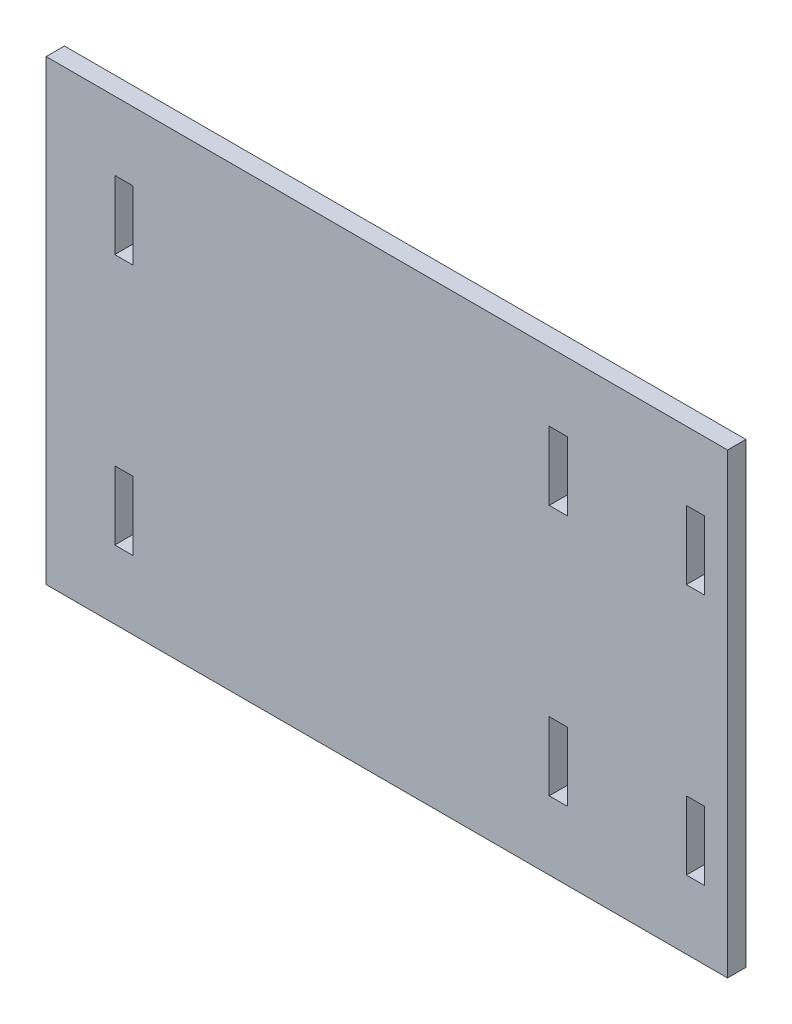
SolidWorks part; units mm, degrees
ref_plane "Front Plane" through (0, 0, 0) normal (0, 0, 1) x (1, 0, 0)
ref_plane "Top Plane" through (0, 0, 0) normal (0, 1, 0) x (1, 0, 0)
ref_plane "Right Plane" through (0, 0, 0) normal (1, 0, 0) x (0, 0, -1)
sketch "Sketch1" plane through (0, 0, 0) normal (0, 0, 1) x (1, 0, 0)
  line L0 (0, 66.0849) -> (0, -70.4198) construction
  line L1 (-64.5, -50) -> (64.5, -50)
  line L3 (-64.5, 50) -> (64.5, 50)
  line L7 (45.5, 35) -> (49.5, 35)
  line L8 (45.5, 35) -> (45.5, 20)
  line L9 (45.5, 20) -> (49.5, 20)
  line L10 (49.5, 35) -> (49.5, 20)
  line L11 (-103.5149, 0) -> (102.2922, 0) construction
  line L12 (45.5, -20) -> (49.5, -20)
  line L13 (45.5, -35) -> (45.5, -20)
  line L14 (49.5, -35) -> (49.5, -20)
  line L15 (45.5, -35) -> (49.5, -35)
  line L16 (-45.5, 35) -> (-49.5, 35)
  line L17 (-45.5, 35) -> (-45.5, 20)
  line L18 (-49.5, 35) -> (-49.5, 20)
  line L19 (-45.5, 20) -> (-49.5, 20)
  line L20 (-45.5, -20) -> (-49.5, -20)
  line L21 (-45.5, -35) -> (-45.5, -20)
  line L22 (-49.5, -35) -> (-49.5, -20)
  line L23 (-45.5, -35) -> (-49.5, -35)
  line L27 (64.5, 50) -> (84.5, 50)
  line L36 (84.5, 50) -> (84.5, -50)
  line L37 (84.5, -50) -> (64.5, -50)
  line L38 (-64.5, -50) -> (-64.5, 50)
  line L39 (75.5, 35) -> (79.5, 35)
  line L40 (75.5, 35) -> (75.5, 20)
  line L41 (75.5, 20) -> (79.5, 20)
  line L42 (79.5, 35) -> (79.5, 20)
  line L43 (75.5, -20) -> (79.5, -20)
  line L44 (75.5, -20) -> (75.5, -35)
  line L45 (75.5, -35) -> (79.5, -35)
  line L46 (79.5, -20) -> (79.5, -35)
  point P0 (0, 0)
  dimension "D1" = 100
  dimension "D2" = 15
  dimension "D3" = 5
  dimension "D4" = 15
  dimension "D5" = 4
  dimension "D6" = 15
  dimension "D7" = 91
  dimension "D8" = 5
  dimension "D9" = 26
  dimension "D10" = 15
extrude "Boss-Extrude1" add sketch "Sketch1" along normal blind 4
